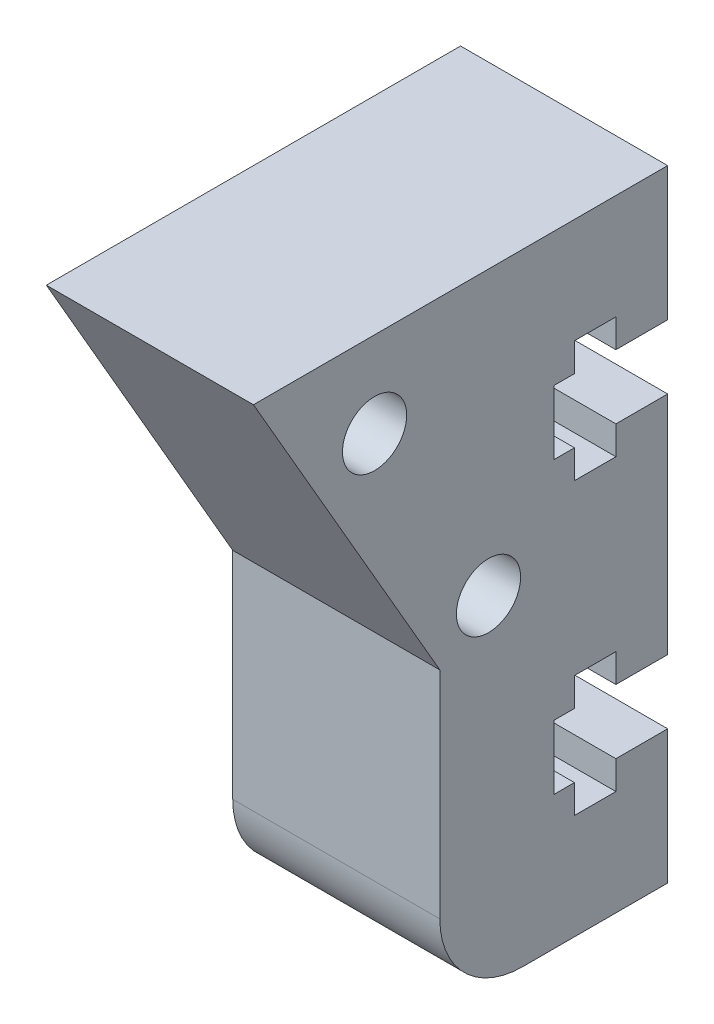
SolidWorks part; units mm, degrees
ref_plane "Płaszczyzna przednia" through (0, 0, 0) normal (0, 0, 1) x (1, 0, 0)
ref_plane "Płaszczyzna górna" through (0, 0, 0) normal (0, 1, 0) x (1, 0, 0)
ref_plane "Płaszczyzna prawa" through (0, 0, 0) normal (1, 0, 0) x (0, 0, -1)
sketch "Szkic1" plane through (0, 0, 0) normal (0, 0, 1) x (1, 0, 0)
  line L0 (180.4349, 79.5308) -> (170.4349, 79.5308)
  line L1 (180.4349, 79.5308) -> (180.4349, 49.5308)
  line L2 (170.4349, 79.5308) -> (170.4349, 49.5308)
  line L3 (180.4349, 49.5308) -> (170.4349, 49.5308)
  dimension "D1" = 10
extrude "Dodanie-wyciągnięcie1" add sketch "Szkic1" along normal blind 30
sketch "Szkic2" plane through (0, 0, 0) normal (0, 0, -1) x (-1, 0, 0)
  line L0 (-175.4349, 69.9808) -> (-175.4349, 73.0808)
  line L1 (-175.4349, 69.9808) -> (-181.9342, 69.9808)
  line L2 (-175.4349, 73.0808) -> (-181.9342, 73.0808)
  line L3 (-181.9342, 69.9808) -> (-181.9342, 73.0808)
  line L4 (-175.4349, 55.9808) -> (-175.4349, 59.0808)
  line L5 (-175.4349, 55.9808) -> (-181.8641, 55.9808)
  line L6 (-175.4349, 59.0808) -> (-181.8641, 59.0808)
  line L7 (-181.8641, 55.9808) -> (-181.8641, 59.0808)
  circle A0 centre (-175.4349, 71.5308) radius 1.55 construction
  circle A2 centre (-175.4349, 57.5308) radius 1.55 construction
  dimension "D1" = 1.55
  dimension "D2" = 3.1
sketch "Szkic3" plane through (180.4349, 0, 0) normal (1, 0, 0) x (0, 0, -1)
  line L0 (0, 73.0808) -> (0, 69.9808)
  line L1 (0, 73.0808) -> (-2.5, 73.0808)
  line L2 (0, 69.9808) -> (-2.5, 69.9808)
  line L3 (-5.5, 73.0808) -> (-5.5, 69.9808)
  line L4 (0, 49.5308) -> (0, 79.5308) construction
  line L5 (-4.5, 74.4558) -> (-2.5, 74.4558)
  line L6 (-4.5, 74.4558) -> (-4.5, 73.0808)
  line L7 (-2.5, 74.4558) -> (-2.5, 73.0808)
  line L8 (-4.5, 68.6058) -> (-2.5, 68.6058)
  line L9 (-2.5, 69.9808) -> (-2.5, 68.6058)
  line L10 (-4.5, 69.9808) -> (-5.5, 69.9808)
  line L11 (-4.5, 69.9808) -> (-4.5, 68.6058)
  line L12 (-4.5, 73.0808) -> (-5.5, 73.0808)
  dimension "D1" = 0
  dimension "D2" = 0
  dimension "D3" = 5.5
  dimension "D4" = 5.85
  dimension "D5" = 1.375
  dimension "D6" = 1
  dimension "D7" = 2
extrude "Wytnij-wyciągnięcie1" cut sketch "Szkic3" against normal blind 10
pattern_linear "Szyk liniowy1" count 2 spacing 14 along (0, -1, 0) of "Wytnij-wyciągnięcie1"
sketch "Szkic4" plane through (180.4349, 0, 0) normal (1, 0, 0) x (0, 0, -1)
  line L0 (-20, 79.5308) -> (-11, 63.9423)
  line L1 (-30, 79.5308) -> (0, 79.5308) construction
  line L3 (-30, 49.5308) -> (-30, 79.5308) construction
  line L6 (-11, 49.5308) -> (-30, 49.5308)
  line L7 (-30, 49.5308) -> (-30, 79.5308)
  line L8 (-30, 79.5308) -> (-20, 79.5308)
  line L9 (-11, 63.9423) -> (-11, 49.5308)
  dimension "D1" = 10
  dimension "D2" = 30
  dimension "D3" = 19
extrude "Wytnij-wyciągnięcie2" cut sketch "Szkic4" against normal blind 10
sketch "Szkic6" plane through (180.4349, 0, 0) normal (1, 0, 0) x (0, 0, -1)
  line L0 (-5.2788, 66.033) -> (-10.475, 63.033) construction
  line L1 (-6.8288, 68.7177) -> (-12.025, 65.7177) construction
  line L4 (-15.975, 72.5593) -> (-10.7788, 75.5593)
  line L5 (-17.525, 75.2439) -> (-12.3288, 78.2439)
  line L6 (-12.025, 65.7177) -> (-6.8288, 68.7177)
  line L7 (-10.475, 63.033) -> (-5.2788, 66.033)
  line L8 (-13.3769, 74.0593) -> (-14.9269, 76.7439)
  line L9 (-7.8769, 64.533) -> (-9.4269, 67.2177)
  circle A0 centre (-8.6519, 65.8753) radius 1.55
  circle A1 centre (-14.1519, 75.4016) radius 1.55
  dimension "D4" = 1.55
  dimension "D1" = 0
  dimension "D2" = 0
  dimension "D3" = 0
sketch "Szkic7" plane through (180.4349, 0, 0) normal (1, 0, 0) x (0, 0, -1)
  circle A0 centre (-8.6519, 65.8753) radius 1.55 construction
  circle A1 centre (-14.1519, 75.4016) radius 1.55 construction
  circle A2 centre (-8.6519, 65.8753) radius 1.55
  circle A3 centre (-14.1519, 75.4016) radius 1.55
extrude "Wytnij-wyciągnięcie4" cut sketch "Szkic7" against normal blind 20
sketch "Szkic8" plane through (180.4349, 0, 0) normal (1, 0, 0) x (0, 0, -1)
  line L5 (-7, 49.5308) -> (-11, 49.5308)
  line L6 (-11, 49.5308) -> (-11, 53.5308)
  arc A0 (-11, 53.5308) -> (-7, 49.5308) centre (-7, 53.5308) ccw
  point P10 (-11, 49.5308)
  dimension "D1" = 4
extrude "Wytnij-wyciągnięcie5" cut sketch "Szkic8" against normal blind 10
equation "\"tolerancja_wpusy\"=0.2"
equation "\"dlugosc_wpustu_duzy\"=20"
equation "\"srednica_otworu_M3\"=3.1"
equation "\"szerokosc_nogi_T\"=3.1"
equation "\"dlugosc_T_30\"=11"
equation "\"grubosc_na_nakretke_kwadrat\"=2"
equation "\"szerokosc_na_nakretke_kwadrat\"=5.85"
equation "\"wyokosc_nadstawki_T\"=0.5"
equation "\"dlugosc_T_20_6\"=14"
equation "\"D4@Szkic3\"=\"szerokosc_na_nakretke_kwadrat\""
equation "\"D5@Szkic3\"=(\"szerokosc_na_nakretke_kwadrat\"-\"szerokosc_nogi_T\")/2"
equation "\"D6@Szkic3\"=\"wyokosc_nadstawki_T\"+0.5"
equation "\"D7@Szkic3\"=\"grubosc_na_nakretke_kwadrat\""
equation "\"D1@Szkic2\"=\"srednica_otworu_M3\"/2"
equation "\"D2@Szkic2\"=\"srednica_otworu_M3\""
